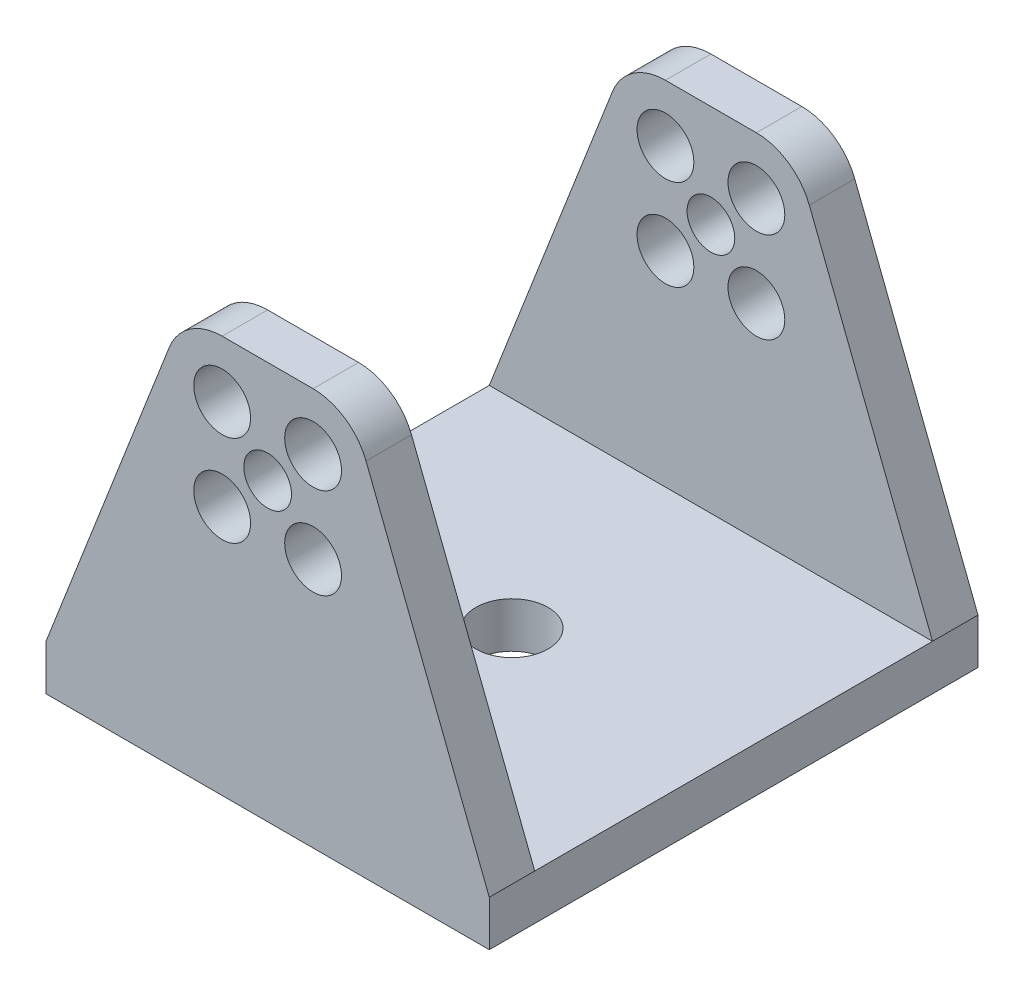
SolidWorks part; units mm, degrees
ref_plane "Front Plane" through (0, 0, 0) normal (0, 0, 1) x (1, 0, 0)
ref_plane "Top Plane" through (0, 0, 0) normal (0, 1, 0) x (1, 0, 0)
ref_plane "Right Plane" through (0, 0, 0) normal (1, 0, 0) x (0, 0, -1)
sketch "Sketch1" plane through (0, 0, 0) normal (0, 1, 0) x (1, 0, 0)
  line L0 (0, 29) -> (39, 0) construction
  line L1 (3.2, 0) -> (35.8, 0)
  line L2 (0, 3.2) -> (0, 25.8)
  line L3 (3.2, 29) -> (35.8, 29)
  line L4 (39, 3.2) -> (39, 25.8)
  line L5 (39, 29) -> (0, 0) construction
  line L7 (3, 26) -> (36, 26) construction
  line L8 (3, 26) -> (3, 3) construction
  line L9 (3, 3) -> (36, 3) construction
  line L10 (36, 26) -> (36, 3) construction
  line L11 (3, 26) -> (36, 3) construction
  line L12 (3, 3) -> (36, 26) construction
  circle A0 centre (19.5, 14.5) radius 3.175
  circle A1 centre (3, 26) radius 1.6
  circle A2 centre (36, 26) radius 1.6
  circle A3 centre (36, 3) radius 1.6
  circle A4 centre (3, 3) radius 1.6
  arc A5 (3.2, 0) -> (0, 3.2) centre (3.2, 3.2) cw
  arc A6 (35.8, 0) -> (39, 3.2) centre (35.8, 3.2) ccw
  arc A7 (35.8, 29) -> (39, 25.8) centre (35.8, 25.8) cw
  arc A8 (0, 25.8) -> (3.2, 29) centre (3.2, 25.8) cw
  dimension "D3" = 6.35
  dimension "D6" = 3.2
  dimension "D7" = 3.2
  dimension "D1" = 39
  dimension "D2" = 29
  dimension "D4" = 33
  dimension "D5" = 23
sketch "Sketch2" plane through (0, 0, 0) normal (0, 1, 0) x (1, 0, 0)
  line L0 (0, 3.2) -> (0, 25.8) construction
  line L1 (0, 36) -> (39, 36)
  line L2 (0, 36) -> (0, -7)
  line L3 (0, -7) -> (39, -7)
  line L4 (39, 36) -> (39, -7)
  line L5 (3.2, 29) -> (35.8, 29) construction
  line L6 (3.2, 0) -> (35.8, 0) construction
  circle A0 centre (19.5, 14.5) radius 3.175
  dimension "D1" = 39
  dimension "D2" = 7
  dimension "D3" = 7
  dimension "D4" = 39
extrude "Boss-Extrude1" add sketch "Sketch2" along normal blind 4
sketch "Sketch3" plane through (0, 0, 0) normal (0, 0, 1) x (1, 0, 0)
  line L0 (19.5, 4) -> (19.5, 38) construction
  line L5 (0, 4) -> (39, 4) construction
  line L6 (0, 4) -> (19.4508, 38) construction
  line L9 (19.4508, 38) -> (19.5492, 38) construction
  line L12 (19.5492, 38) -> (39, 4) construction
  line L15 (39, 4) -> (28.1587, 31.8157)
  line L16 (23.5, 35) -> (15.5, 35)
  line L17 (39, 4) -> (0, 4)
  line L18 (0, 4) -> (10.8413, 31.8157)
  arc A0 (4.2977, 11.5124) -> (34.7023, 11.5124) centre (19.5, 26) ccw construction
  circle A1 centre (15.5, 30) radius 2.5
  circle A2 centre (23.5, 30) radius 2.5
  circle A3 centre (23.5, 22) radius 2.5
  circle A4 centre (15.5, 22) radius 2.5
  circle A5 centre (19.5, 26) radius 2.1
  arc A6 (28.1587, 31.8157) -> (23.5, 35) centre (23.5, 30) ccw
  arc A7 (10.8413, 31.8157) -> (15.5, 35) centre (15.5, 30) cw
  point P27 (19.5, 35)
  dimension "D2" = 42
  dimension "D3" = 5
  dimension "D8" = 4.2
  dimension "D12" = 5
  dimension "D1" = 22
  dimension "D4" = 4
  dimension "D5" = 4
  dimension "D9" = 12
  dimension "D10" = 5
  dimension "D11" = 4
  dimension "D6" = 2
  dimension "D7" = 2
extrude "Boss-Extrude2" add sketch "Sketch3" along normal up to surface and the other way up to surface up to face at (19.5, 2, 7) other way up to face at (19.5, 2, -36)
sketch "Sketch5" plane through (0, 0, 0) normal (1, 0, 0) x (0, 0, -1)
  line L0 (36, 4) -> (-7, 4) construction
  line L1 (32, 4) -> (-3, 4)
  line L2 (32, 4) -> (32, 48.5592)
  line L3 (32, 48.5592) -> (-3, 48.5592)
  line L4 (-3, 4) -> (-3, 48.5592)
  line L5 (36, 4) -> (36, 31.8157) construction
  line L6 (-7, 4) -> (-7, 31.8157) construction
  dimension "D1" = 4
  dimension "D2" = 4
extrude "Cut-Extrude2" cut sketch "Sketch5" along normal through all
